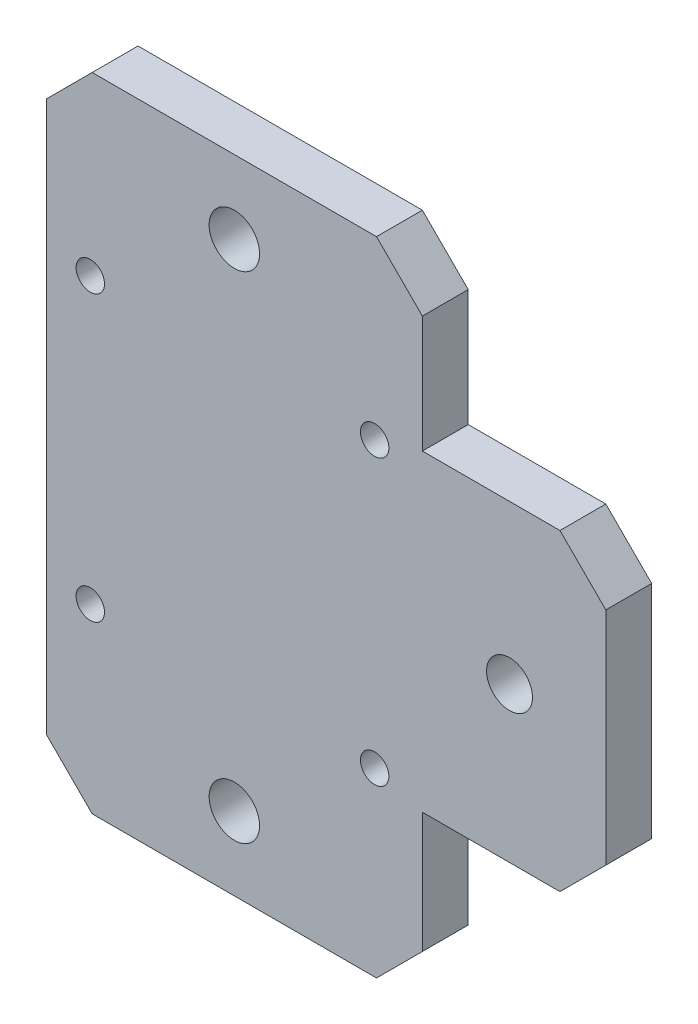
SolidWorks part; units mm, degrees
ref_plane "Front Plane" through (0, 0, 0) normal (0, 0, 1) x (1, 0, 0)
ref_plane "Top Plane" through (0, 0, 0) normal (0, 1, 0) x (1, 0, 0)
ref_plane "Right Plane" through (0, 0, 0) normal (1, 0, 0) x (0, 0, -1)
sketch "Sketch1" plane through (0, 0, 0) normal (0, 0, 1) x (1, 0, 0)
  line L0 (20.5, -35) -> (-20.5, -35)
  line L5 (20.5, -35) -> (20.5, 35)
  line L6 (20.5, 35) -> (-20.5, 35)
  line L7 (-20.5, -35) -> (-20.5, 35)
  line L8 (20.5, -35) -> (-20.5, 35) construction
  line L9 (20.5, 35) -> (-20.5, -35) construction
  circle A0 centre (-15.7048, -15.2952) radius 1.55
  circle A1 centre (15.2952, -15.2952) radius 1.55
  circle A2 centre (15.2952, 15.7048) radius 1.55
  circle A3 centre (-15.7048, 15.7048) radius 1.55
  circle A4 centre (0, 27) radius 2.75
  circle A5 centre (0, -27) radius 2.75
  point P9 (0, 0)
  dimension "D5" = 5.5
  dimension "D6" = 5.5
  dimension "D9" = 3.1
  dimension "D1" = 70
  dimension "D2" = 31
  dimension "D3" = 31
  dimension "D4" = 41
  dimension "D7" = 8
  dimension "D8" = 8
extrude "Boss-Extrude1" add sketch "Sketch1" along normal blind 5
chamfer "Chamfer1" distance 5 angle 45 4 edges at (-20.5, -35, 2.5) (20.5, -35, 2.5) (-20.5, 35, 2.5) (20.5, 35, 2.5)
sketch "Sketch2" plane through (0, 0, 5) normal (0, 0, 1) x (1, 0, 0)
  line L0 (20.5, -30) -> (20.5, 30) construction
  line L1 (20.5, 17.2548) -> (40.5, 17.2548)
  line L2 (20.5, 17.2548) -> (20.5, -16.8452)
  line L3 (20.5, -16.8452) -> (40.5, -16.8452)
  line L4 (40.5, 17.2548) -> (40.5, -16.8452)
  circle A0 centre (30, 0) radius 2.5
  dimension "D3" = 5
  dimension "D1" = 20
  dimension "D2" = 30
extrude "Boss-Extrude2" add sketch "Sketch2" against normal blind 5 contours L1 L4 L3 L2
chamfer "Chamfer2" distance 5 angle 45 2 edges at (40.5, -16.8452, 2.5) (40.5, 17.2548, 2.5)
